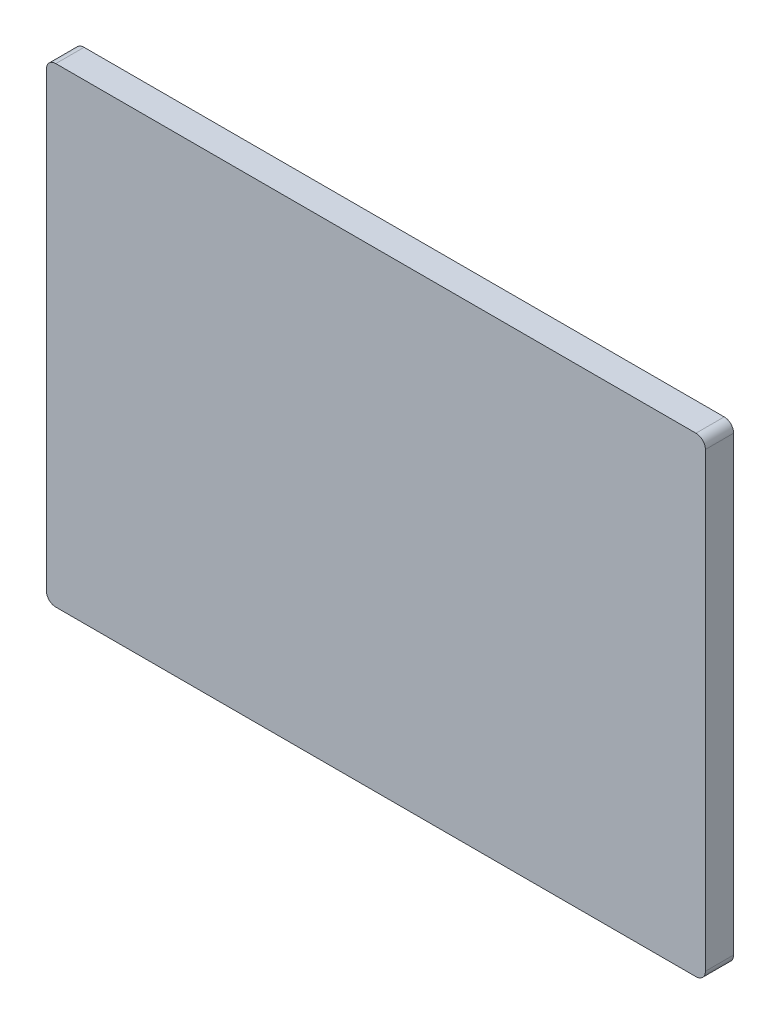
SolidWorks part; units mm, degrees
ref_plane "Plan de face" through (0, 0, 0) normal (0, 0, 1) x (1, 0, 0)
ref_plane "Plan de dessus" through (0, 0, 0) normal (0, 1, 0) x (1, 0, 0)
ref_plane "Plan de droite" through (0, 0, 0) normal (1, 0, 0) x (0, 0, -1)
sketch "Esquisse1" plane through (0, 0, 0) normal (0, 0, 1) x (1, 0, 0)
  line L1 (175, -125) -> (-175, -125)
  line L2 (175, -125) -> (175, 125)
  line L3 (175, 125) -> (-175, 125)
  line L4 (-175, -125) -> (-175, 125)
  line L5 (175, -125) -> (-175, 125) construction
  line L6 (175, 125) -> (-175, -125) construction
  point P0 (0, 0)
  dimension "D1" = 350
  dimension "D2" = 250
extrude "Boss.-Extru.1" add sketch "Esquisse1" along normal blind 15
fillet "Congé1" radius 5 4 edges at (175, -125, 7.5) (-175, -125, 7.5) (-175, 125, 7.5) (175, 125, 7.5)
